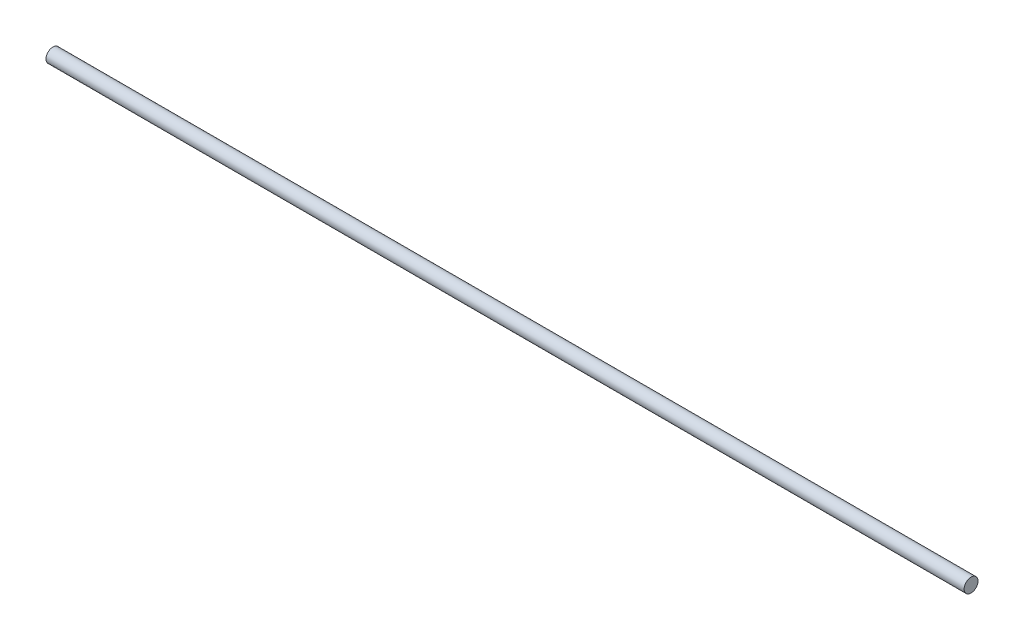
SolidWorks part; units mm, degrees
material "6061-T6 (SS)"
ref_plane "Front Plane" through (0, 0, 0) normal (1, 0, 0) x (0, 1, 0)
ref_plane "Top Plane" through (0, 0, 0) normal (0, 0, 1) x (0, 1, 0)
ref_plane "Right Plane" through (0, 0, 0) normal (0, 1, 0) x (-1, 0, 0)
sketch "Sketch1" plane through (0, 0, 0) normal (1, 0, 0) x (0, 1, 0)
  circle A0 centre (0, 0) radius 4.7625
  dimension "D1" = 9.525
extrude "Boss-Extrude1" add sketch "Sketch1" along normal blind 631.19
equation "\"F\"= 400"
equation "\"E\"= 10000000"
equation "\"def\"= 0.009"
equation "\"d\"= 0.375"
equation "\"A\"= 3.141592654 * \"d\" ^ 2 / 4"
equation "\"L\"= \"def\" * \"A\" * \"E\" / \"F\""
